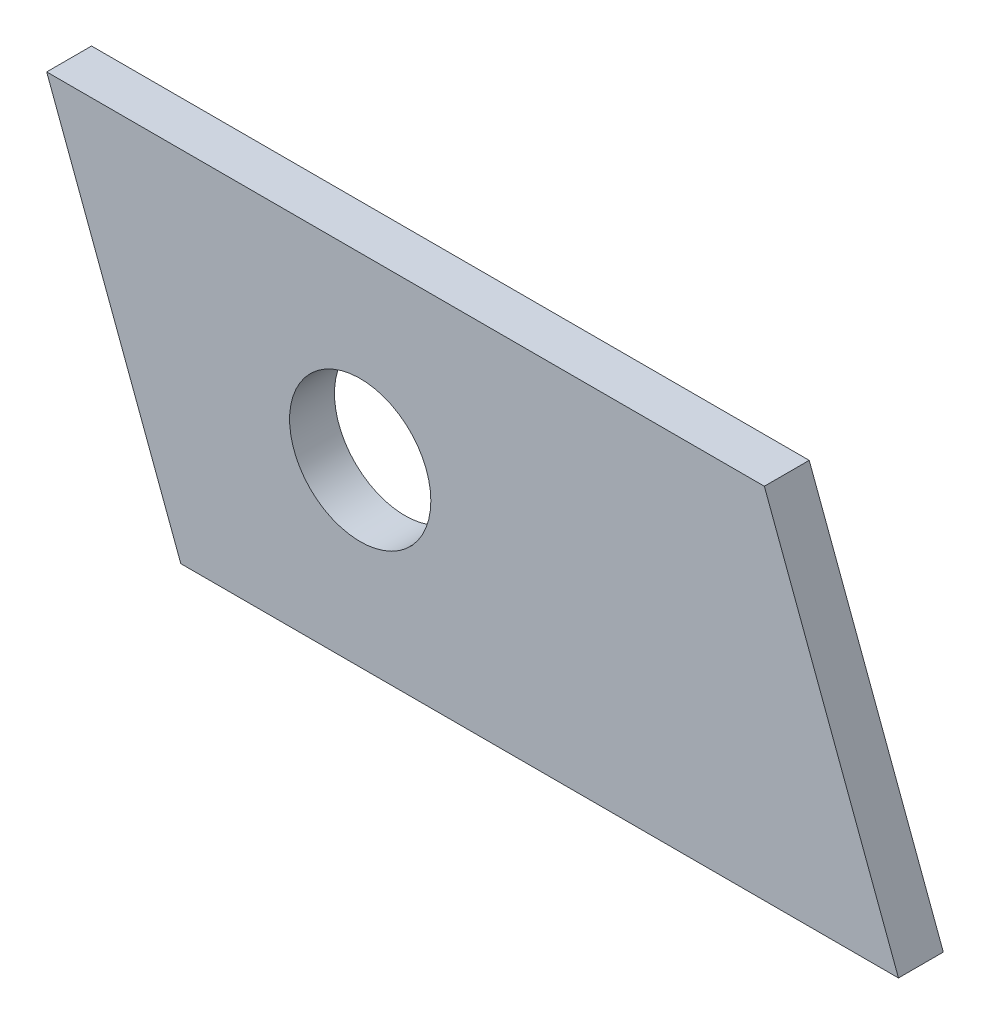
SolidWorks part; units mm, degrees
material "Plain Carbon Steel"
ref_plane "Front Plane" through (0, 0, 0) normal (0, 0, 1) x (1, 0, 0)
ref_plane "Top Plane" through (0, 0, 0) normal (0, 1, 0) x (1, 0, 0)
ref_plane "Right Plane" through (0, 0, 0) normal (1, 0, 0) x (0, 0, -1)
sketch "Sketch1" plane through (0, 0, 0) normal (0, 0, 1) x (1, 0, 0)
  line L0 (-218.7069, 117.1731) -> (-209.2135, 91.7731)
  line L1 (-209.2135, 91.7731) -> (-158.4135, 91.7731)
  line L3 (-167.9069, 117.1731) -> (-218.7069, 117.1731)
  line L4 (273.2879, 91.7731) -> (-222.7716, 91.7731) construction
  line L7 (-196.5135, 117.1731) -> (-196.5135, 91.7731) construction
  line L8 (-213.9602, 104.4731) -> (-163.1602, 104.4731) construction
  line L10 (-209.2135, 91.7731) -> (-323.1338, 396.5731) construction
  line L12 (-167.9069, 117.1731) -> (-158.4135, 91.7731)
  circle A0 centre (-196.5135, 104.4731) radius 5
  point P3 (-158.8994, 104.4731)
  point P6 (-154.1527, 91.7731)
  point P7 (-154.2002, 91.9001)
  point P16 (-193.3069, 91.7731)
  point P17 (0, 0)
  point P18 (-188.5602, 104.4731)
  point P19 (-196.5135, 117.1731)
  dimension "D2" = 10
  dimension "D1" = 25.4
  dimension "D3" = 50.8
  dimension "D4" = 12.7
extrude "Boss-Extrude1" add sketch "Sketch1" against normal blind 3.175
